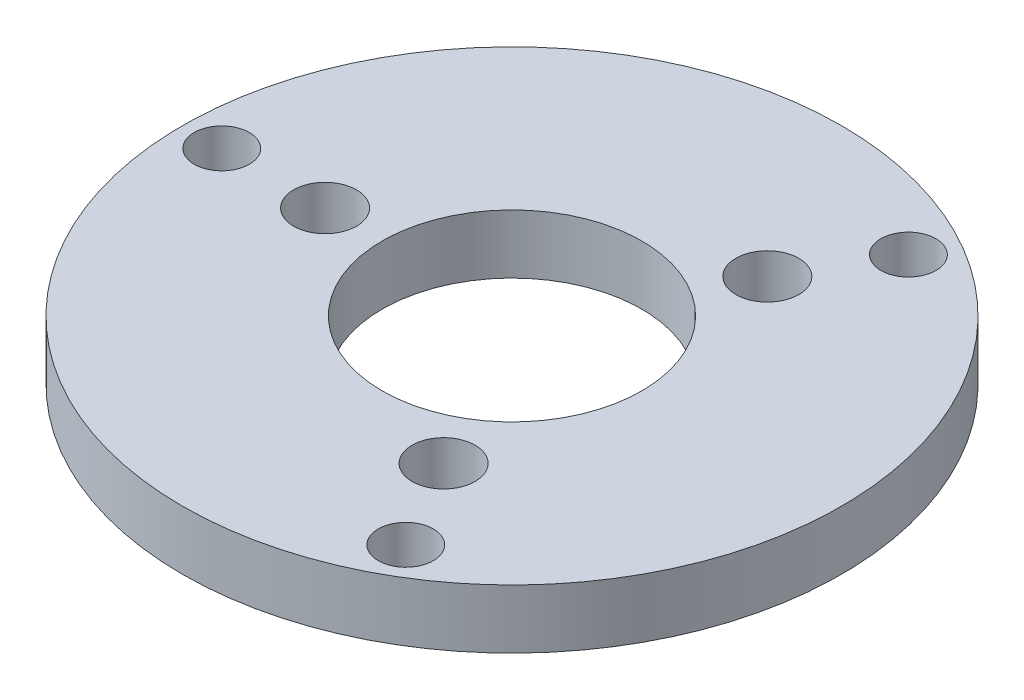
SolidWorks part; units mm, degrees
ref_plane "前视基准面" through (0, 0, 0) normal (0, 0, 1) x (1, 0, 0)
ref_plane "上视基准面" through (0, 0, 0) normal (0, 1, 0) x (1, 0, 0)
ref_plane "右视基准面" through (0, 0, 0) normal (1, 0, 0) x (0, 0, -1)
sketch "草图1" plane through (0, 0, 0) normal (0, 1, 0) x (1, 0, 0)
  circle A0 centre (0, 0) radius 16.75
  dimension "D1" = 33.5
extrude "凸台-拉伸1" add sketch "草图1" along normal blind 3
sketch "草图2" plane through (0, 3, 0) normal (0, 1, 0) x (1, 0, 0)
  line L0 (0, 0) -> (4.75, 8.2272)
  line L1 (0, 0) -> (4.75, 8.2272) construction
  line L2 (0, 0) -> (10.1113, 0)
  circle A0 centre (4.75, 8.2272) radius 1.6
  circle A2 centre (4.75, -8.2272) radius 1.6
  circle A3 centre (-9.5, 0) radius 1.6
  dimension "D1" = 3.2
  dimension "D2" = 60
  dimension "D5" = 9.5
  dimension "D3" = 3
extrude "切除-拉伸1" cut sketch "草图2" against normal blind 3 contours A2 | A0 | A3
sketch "草图3" plane through (0, 3, 0) normal (0, 1, 0) x (1, 0, 0)
  circle A0 centre (0, 0) radius 6.6
  dimension "D1" = 13.2
extrude "切除-拉伸2" cut sketch "草图3" against normal blind 3
sketch "草图4" plane through (0, 3, 0) normal (0, 1, 0) x (1, 0, 0)
  line L0 (-14.75, 0) -> (0, 0)
  line L1 (0, 0) -> (-14.75, 0) construction
  circle A0 centre (-14.75, 0) radius 1.4
  circle A1 centre (7.375, 12.7739) radius 1.4
  circle A2 centre (7.375, -12.7739) radius 1.4
  dimension "D1" = 2.8
  dimension "D2" = 14.75
  dimension "D5" = 14.75
  dimension "D4" = 14.75
  dimension "D3" = 3
extrude "切除-拉伸3" cut sketch "草图4" against normal blind 10 contours A2 | A1 | A0
